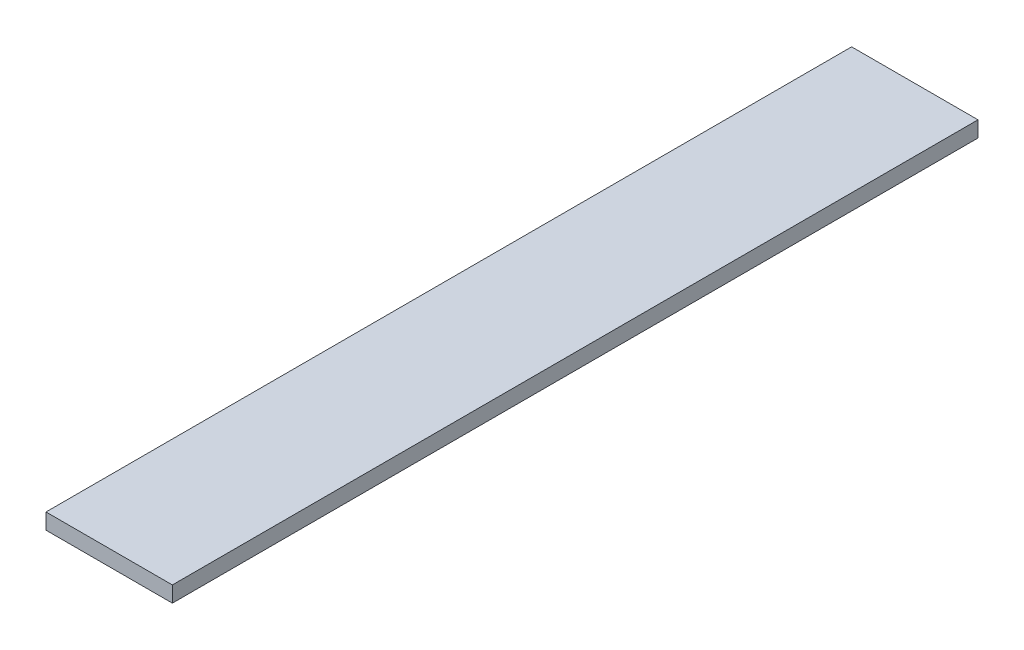
SolidWorks part; units mm, degrees
ref_plane "Front Plane" through (0, 0, 0) normal (0, 0, 1) x (1, 0, 0)
ref_plane "Top Plane" through (0, 0, 0) normal (0, 1, 0) x (1, 0, 0)
ref_plane "Right Plane" through (0, 0, 0) normal (1, 0, 0) x (0, 0, -1)
sketch "Sketch1" plane through (0, 0, 0) normal (0, 1, 0) x (1, 0, 0)
  line L1 (-50.8, 323.85) -> (50.8, 323.85)
  line L2 (-50.8, 323.85) -> (-50.8, -323.85)
  line L3 (-50.8, -323.85) -> (50.8, -323.85)
  line L4 (50.8, 323.85) -> (50.8, -323.85)
  line L5 (-50.8, 323.85) -> (50.8, -323.85) construction
  line L6 (-50.8, -323.85) -> (50.8, 323.85) construction
  point P0 (0, 0)
  dimension "D1" = 647.7
  dimension "D2" = 101.6
extrude "Boss-Extrude1" add sketch "Sketch1" along normal blind 12.7
